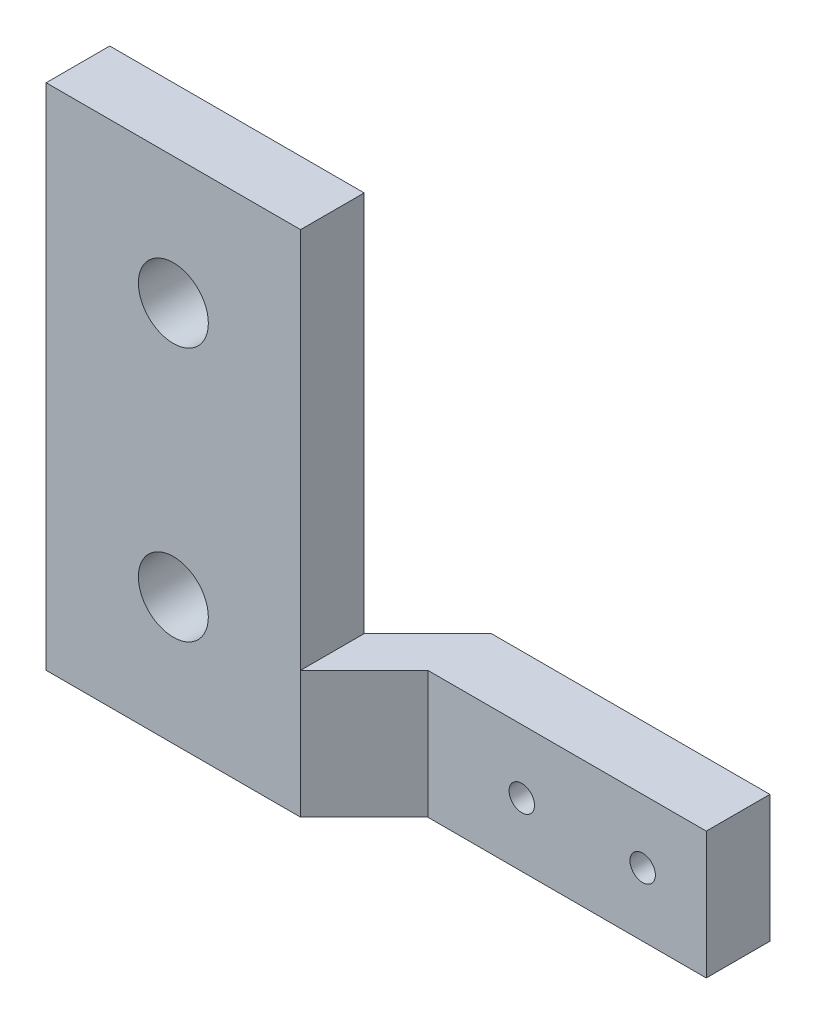
SolidWorks part; units mm, degrees
ref_plane "Plan de face" through (0, 0, 0) normal (0, 0, 1) x (1, 0, 0)
ref_plane "Plan de dessus" through (0, 0, 0) normal (0, 1, 0) x (1, 0, 0)
ref_plane "Plan de droite" through (0, 0, 0) normal (1, 0, 0) x (0, 0, -1)
sketch "Esquisse1" plane through (0, 0, 0) normal (0, 0, 1) x (1, 0, 0)
  line L0 (-27.8251, 6.7177) -> (-27.8251, -13.2823) construction
  line L2 (-37.8251, 16.7177) -> (-37.8251, -23.2823)
  line L8 (-37.8251, 16.7177) -> (-17.8251, 16.7177)
  line L9 (-17.8251, 16.7177) -> (-17.8251, -23.2823)
  line L12 (-37.8251, -23.2823) -> (-17.8251, -23.2823)
  circle A0 centre (-27.8251, 6.7177) radius 2.75
  circle A1 centre (-27.8251, -13.2823) radius 2.75
  point P1 (1.788, -12.3389)
  point P6 (0, 0)
  point P8 (-27.8251, -3.2823)
  point P10 (-37.8251, -3.2823)
  point P11 (0, 0)
  point P16 (2.1749, -8.6077)
  point P17 (-27.8251, 16.7177)
  dimension "D3" = 5.5
  dimension "D1" = 20
  dimension "D2" = 40
  dimension "D5" = 20
extrude "Boss.-Extru.1" add sketch "Esquisse1" along normal blind 5
sketch "Esquisse2" plane through (0, -23.2823, 0) normal (0, -1, 0) x (1, 0, 0)
  line L0 (-17.8251, 0) -> (-17.8251, 5)
  line L1 (-17.8251, 5) -> (-12.8251, 0)
  line L2 (-12.8251, 0) -> (9.0631, 0)
  line L3 (9.0631, 0) -> (9.0631, -5)
  line L4 (9.0631, -5) -> (-12.8251, -5)
  line L5 (-12.8251, -5) -> (-17.8251, 0)
  point P4 (-12.4648, 5.3604)
  dimension "D1" = 45
  dimension "D2" = 5
  dimension "D3" = 5
extrude "Boss.-Extru.2" add sketch "Esquisse2" against normal blind 10
sketch "Esquisse3" plane through (0, 0, 0) normal (0, 0, 1) x (1, 0, 0)
  line L0 (4.0631, -18.2823) -> (-5.4369, -18.2823) construction
  line L1 (9.0631, -13.2823) -> (9.0631, -23.2823) construction
  line L2 (9.0631, -13.2823) -> (-12.8251, -13.2823) construction
  circle A0 centre (4.0631, -18.2823) radius 1
  circle A1 centre (-5.4369, -18.2823) radius 1
  dimension "D4" = 2
  dimension "D1" = 9.5
  dimension "D2" = 5
  dimension "D3" = 5
extrude "Enlèv. mat.-Extru.1" cut sketch "Esquisse3" against normal up to next
